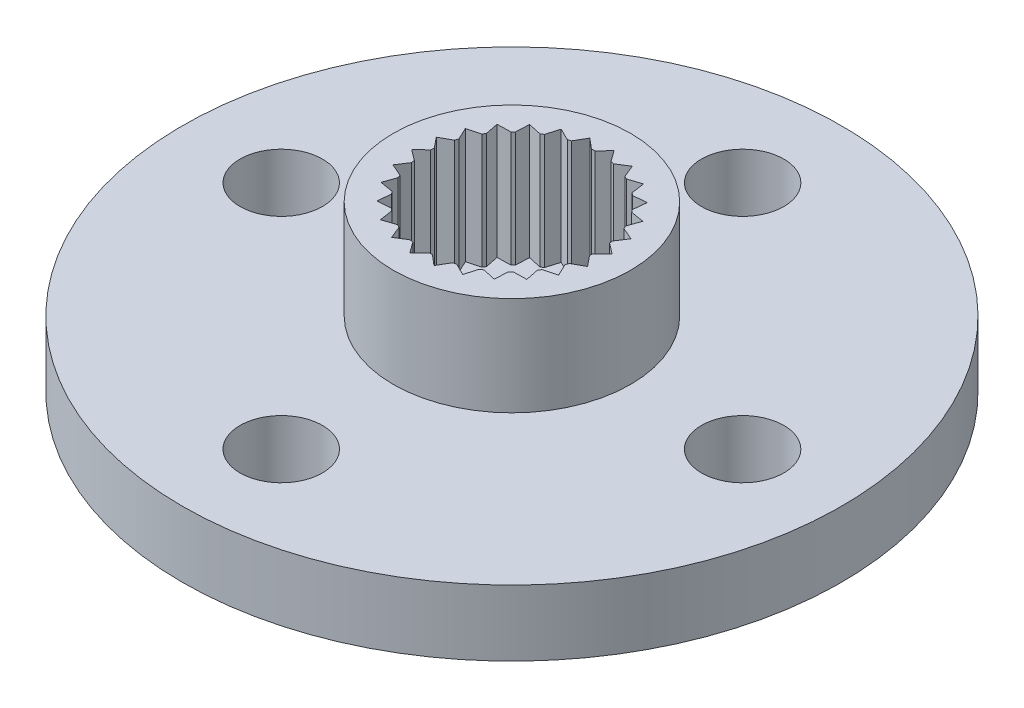
SolidWorks part; units mm, degrees
ref_plane "Front Plane" through (0, 0, 0) normal (0, 0, 1) x (1, 0, 0)
ref_plane "Top Plane" through (0, 0, 0) normal (0, 1, 0) x (1, 0, 0)
ref_plane "Right Plane" through (0, 0, 0) normal (1, 0, 0) x (0, 0, -1)
sketch "Sketch1" plane through (0, 0, 0) normal (0, 0, 1) x (1, 0, 0)
  line L0 (2.3451, 2) -> (1.5, 2)
  line L1 (1.5, 0) -> (10, 0)
  line L2 (10, 0) -> (10, 2)
  line L3 (10, 2) -> (3.6, 2)
  line L4 (3.6, 2) -> (3.6, 5)
  line L5 (3.6, 5) -> (2.3451, 5)
  line L6 (2.3451, 5) -> (2.3451, 2)
  line L7 (1.5, 2) -> (1.5, 0)
  line L8 (0, 6.7953) -> (0, -4.2724) construction
  dimension "D1" = 1.5
  dimension "D2" = 10
  dimension "D3" = 2
  dimension "D4" = 3
  dimension "D5" = 3.6
revolve "Revolve1" add sketch "Sketch1" angle 360 about L8
sketch "Sketch2" plane through (0, 2, 0) normal (0, 1, 0) x (1, 0, 0)
  circle A1 centre (0, 0) radius 7
  point P3 (-7, 0)
  point P5 (0, 7)
  point P6 (7, 0)
  point P7 (0, -7)
  dimension "D1" = 14
hole_wizard "M3 Tapped Hole1" positions "Sketch3" profile "Sketch4" tap size "M3" standard "DIN" end condition through all
sketch "Sketch3" plane through (0, 2, 0) normal (0, 1, 0) x (1, 0, 0)
  point P0 (-7, 0)
  point P3 (0, 7)
  point P6 (7, 0)
  point P9 (0, -7)
sketch "Sketch4" plane through (-7, 2, 0) normal (1, 0, 0) x (0, 0, 1)
  line L0 (0, 0) -> (0, 2)
  line L1 (0, 2) -> (1.25, 2)
  line L2 (1.25, 2) -> (1.25, 0)
  line L5 (1.25, 0) -> (0, 0)
  line L11 (0, -6.35) -> (0, 107.95) construction
  dimension "Thru Tap Drill Dia." = 2.5
  dimension "Thru Tap Drill Depth" = 2
cosmetic thread "Hole Thread1" parameters "D2"=3
cosmetic thread "Hole Thread2" parameters "D2"=3
cosmetic thread "Hole Thread3" parameters "D2"=3
cosmetic thread "Hole Thread4" parameters "D2"=3
sketch "Sketch5" plane through (0, 5, 0) normal (0, 1, 0) x (1, 0, 0)
  line L0 (-1.3656, 2.2125) -> (-1.7649, 2.3011)
  line L1 (-1.7649, 2.3011) -> (-1.7828, 1.8925)
  line L2 (-1.7828, 1.8925) -> (-1.8554, 1.8214)
  line L3 (-1.8554, 1.8214) -> (-2.2643, 1.8119)
  line L4 (-2.2643, 1.8119) -> (-2.1839, 1.4109)
  line L5 (-2.1839, 1.4109) -> (-2.2374, 1.3245)
  line L6 (-2.2374, 1.3245) -> (-2.6321, 1.2174)
  line L7 (-2.6321, 1.2174) -> (-2.4581, 0.8472)
  line L8 (-2.4581, 0.8472) -> (-2.4893, 0.7506)
  line L9 (-2.4893, 0.7506) -> (-2.847, 0.5521)
  line L10 (-2.847, 0.5521) -> (-2.5894, 0.2344)
  line L11 (-2.5894, 0.2344) -> (-2.5966, 0.133)
  line L12 (-2.5966, 0.133) -> (-2.8964, -0.1453)
  line L13 (-2.8964, -0.1453) -> (-2.5703, -0.3921)
  line L14 (-2.5703, -0.3921) -> (-2.553, -0.4923)
  line L15 (-2.553, -0.4923) -> (-2.7774, -0.8342)
  line L16 (-2.7774, -0.8342) -> (-2.4017, -0.9959)
  line L17 (-2.4017, -0.9959) -> (-2.361, -1.0889)
  line L18 (-2.361, -1.0889) -> (-2.4971, -1.4746)
  line L19 (-2.4971, -1.4746) -> (-2.0936, -1.5417)
  line L20 (-2.0936, -1.5417) -> (-2.0318, -1.6223)
  line L21 (-2.0318, -1.6223) -> (-2.0716, -2.0294)
  line L22 (-2.0716, -2.0294) -> (-1.6638, -1.9979)
  line L23 (-1.6638, -1.9979) -> (-1.5845, -2.0614)
  line L24 (-1.5845, -2.0614) -> (-1.5258, -2.4662)
  line L25 (-1.5258, -2.4662) -> (-1.1373, -2.338)
  line L26 (-1.1373, -2.338) -> (-1.0451, -2.3807)
  line L27 (-1.0451, -2.3807) -> (-0.8912, -2.7597)
  line L28 (-0.8912, -2.7597) -> (-0.5448, -2.5423)
  line L29 (-0.5448, -2.5423) -> (-0.445, -2.5616)
  line L30 (-0.445, -2.5616) -> (-0.2049, -2.8928)
  line L31 (-0.2049, -2.8928) -> (0.0795, -2.5988)
  line L32 (0.0795, -2.5988) -> (0.1809, -2.5937)
  line L33 (0.1809, -2.5937) -> (0.4933, -2.8577)
  line L34 (0.4933, -2.8577) -> (0.6991, -2.5042)
  line L35 (0.6991, -2.5042) -> (0.7964, -2.475)
  line L36 (0.7964, -2.475) -> (1.1629, -2.6566)
  line L38 (1.1629, -2.6566) -> (1.2781, -2.2642)
  line L39 (1.2781, -2.2642) -> (1.3656, -2.2125)
  line L40 (1.3656, -2.2125) -> (1.7649, -2.3011)
  line L41 (1.7649, -2.3011) -> (1.7828, -1.8925)
  line L42 (1.7828, -1.8925) -> (1.8554, -1.8214)
  line L43 (1.8554, -1.8214) -> (2.2643, -1.8119)
  line L44 (2.2643, -1.8119) -> (2.1839, -1.4109)
  line L45 (2.1839, -1.4109) -> (2.2374, -1.3245)
  line L46 (2.2374, -1.3245) -> (2.6321, -1.2174)
  line L47 (2.6321, -1.2174) -> (2.4581, -0.8472)
  line L48 (2.4581, -0.8472) -> (2.4893, -0.7506)
  line L49 (2.4893, -0.7506) -> (2.847, -0.5521)
  line L50 (2.847, -0.5521) -> (2.5894, -0.2344)
  line L51 (2.5894, -0.2344) -> (2.5966, -0.133)
  line L52 (2.5966, -0.133) -> (2.8964, 0.1453)
  line L53 (2.8964, 0.1453) -> (2.5703, 0.3921)
  line L54 (2.5703, 0.3921) -> (2.553, 0.4923)
  line L55 (2.553, 0.4923) -> (2.7774, 0.8342)
  line L56 (2.7774, 0.8342) -> (2.4017, 0.9959)
  line L57 (2.4017, 0.9959) -> (2.361, 1.0889)
  line L58 (2.361, 1.0889) -> (2.4971, 1.4746)
  line L59 (2.4971, 1.4746) -> (2.0936, 1.5417)
  line L60 (2.0936, 1.5417) -> (2.0318, 1.6223)
  line L61 (2.0318, 1.6223) -> (2.0716, 2.0294)
  line L62 (2.0716, 2.0294) -> (1.6638, 1.9979)
  line L63 (1.6638, 1.9979) -> (1.5845, 2.0614)
  line L64 (1.5845, 2.0614) -> (1.5258, 2.4662)
  line L65 (1.5258, 2.4662) -> (1.1373, 2.338)
  line L66 (1.1373, 2.338) -> (1.0451, 2.3807)
  line L67 (1.0451, 2.3807) -> (0.8912, 2.7597)
  line L68 (0.8912, 2.7597) -> (0.5448, 2.5423)
  line L69 (0.5448, 2.5423) -> (0.445, 2.5616)
  line L70 (0.445, 2.5616) -> (0.2049, 2.8928)
  line L71 (0.2049, 2.8928) -> (-0.0795, 2.5988)
  line L72 (-0.0795, 2.5988) -> (-0.1809, 2.5937)
  line L73 (-0.1809, 2.5937) -> (-0.4933, 2.8577)
  line L74 (-0.4933, 2.8577) -> (-0.6991, 2.5042)
  line L75 (-0.6991, 2.5042) -> (-0.7964, 2.475)
  line L76 (-0.7964, 2.475) -> (-1.1629, 2.6566)
  line L77 (-1.1629, 2.6566) -> (-1.2781, 2.2642)
  line L78 (-1.2781, 2.2642) -> (-1.3656, 2.2125)
extrude "Cut-Extrude1" cut sketch "Sketch5" against normal blind 3.5
